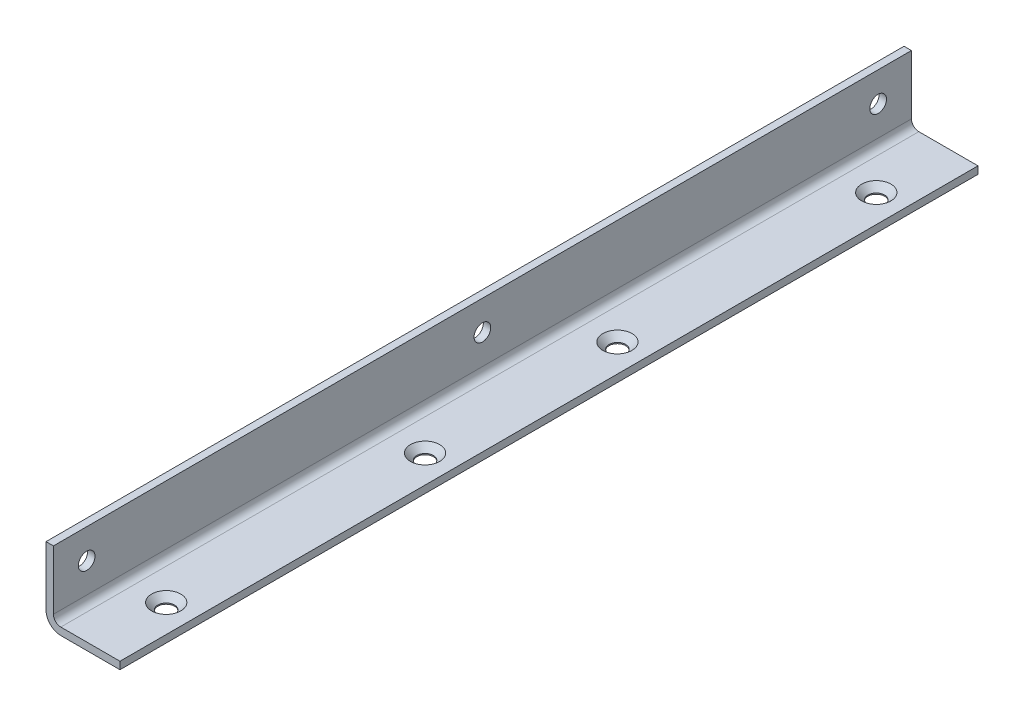
SolidWorks part; units mm, degrees
ref_plane "Спереди" through (0, 0, 0) normal (0, 0, 1) x (1, 0, 0)
ref_plane "Сверху" through (0, 0, 0) normal (0, 1, 0) x (1, 0, 0)
ref_plane "Справа" through (0, 0, 0) normal (1, 0, 0) x (0, 0, -1)
sketch "Эскиз1" plane through (0, 0, 0) normal (0, 0, 1) x (1, 0, 0)
  line L1 (0, 0) -> (20, 0)
  line L2 (0, 0) -> (0, 20)
  line L3 (0, 20) -> (2, 20)
  line L4 (20, 0) -> (20, 2)
  line L5 (4, 2) -> (20, 2)
  line L6 (2, 4) -> (2, 20)
  arc A0 (4, 2) -> (2, 4) centre (4, 4) cw
  dimension "D5" = 2
  dimension "D1" = 20
  dimension "D2" = 20
  dimension "D3" = 2
  dimension "D4" = 2
extrude "Вытянуть1" add sketch "Эскиз1" along normal blind 232
sketch "Эскиз2" plane through (2, 0, 0) normal (1, 0, 0) x (0, 0, -1)
  line L0 (-116, 12) -> (-116, 74.4355) construction
  line L2 (-232, 4) -> (-232, 20) construction
  line L3 (-280.1291, 12) -> (26.6955, 12) construction
  line L4 (-232, 20) -> (0, 20) construction
  line L5 (0, 4) -> (0, 20) construction
  circle A0 centre (-223, 12) radius 2.25
  circle A1 centre (-9, 12) radius 2.25
  circle A2 centre (-116, 12) radius 2.25
  dimension "D2" = 4.5
  dimension "D5" = 107
  dimension "D4" = 214
  dimension "D1" = 8
extrude "Вырез-Вытянуть1" cut sketch "Эскиз2" against normal blind 10
sketch "Эскиз3" plane through (0, 2, 0) normal (0, 1, 0) x (1, 0, 0)
  line L0 (-101.7059, -116) -> (103.8615, -116) construction
  line L1 (20, 0) -> (4, 0) construction
  line L2 (20, -232) -> (4, -232) construction
  line L4 (12.5, -212) -> (12.5, -20) construction
  line L5 (20, -232) -> (20, 0) construction
  circle A1 centre (12.5, -212) radius 2.25
  circle A2 centre (12.5, -142) radius 2.25
  circle A5 centre (12.5, -20) radius 2.25
  circle A8 centre (12.5, -90) radius 2.25
  dimension "D1" = 70
  dimension "D2" = 4.5
  dimension "D3" = 7.5
  dimension "D4" = 20
  dimension "D5" = 52
extrude "Вырез-Вытянуть2" cut sketch "Эскиз3" against normal blind 10
chamfer "Фаска1" distance 1.7 angle 45 4 edges at (12.5, 2, 17.75) (12.5, 2, 92.25) (12.5, 2, 139.75) (12.5, 2, 214.25)
fillet "Скругление1" radius 4 1 edges at (0, 0, 116)
